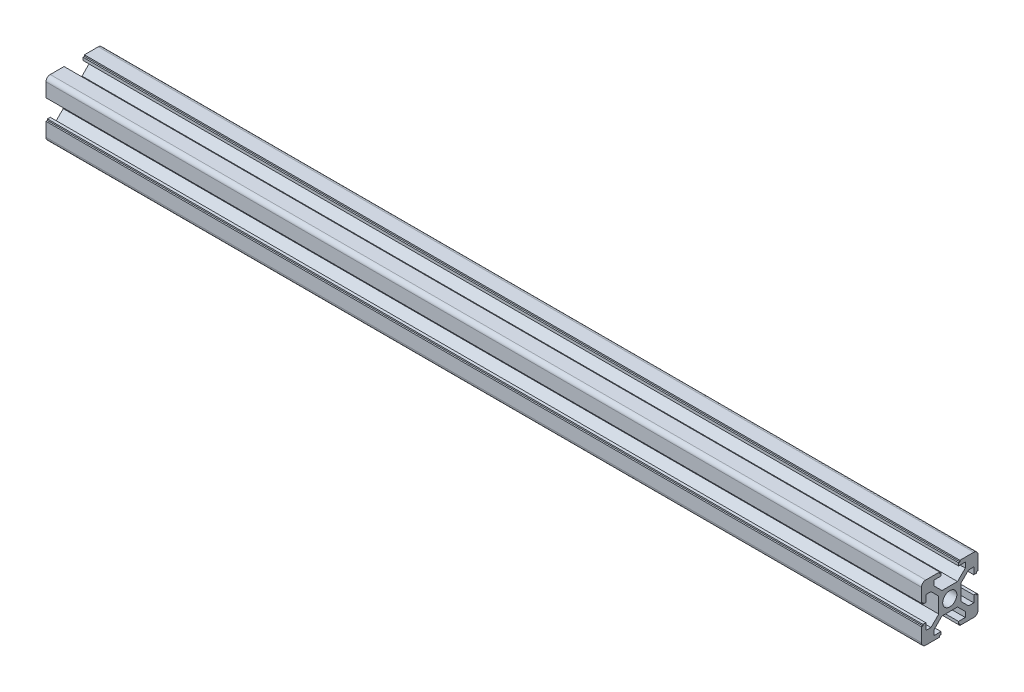
SolidWorks part; units mm, degrees
ref_plane "前视基准面" through (0, 0, 0) normal (0, 0, 1) x (1, 0, 0)
ref_plane "上视基准面" through (0, 0, 0) normal (0, 1, 0) x (1, 0, 0)
ref_plane "右视基准面" through (0, 0, 0) normal (1, 0, 0) x (0, 0, -1)
sketch "草图1" plane through (0, 0, 0) normal (0, 1, 0) x (1, 0, 0)
  line L0 (0, 0) -> (310, 0)
  dimension "D1" = 310
other "铝型材 20 X 20 X R1.5(1)"
ref_plane "基准面1" through (0, 0, 0) normal (1, 0, 0) x (0, 0, -1)
sketch "Sketch1" plane through (0, 0, 0) normal (1, 0, 0) x (0, 0, -1)
  line L0 (-3.6, 10) -> (-3.6, 9.5)
  line L1 (-3.6, 9.5) -> (-3.1, 9.5)
  line L2 (-3.1, 9.5) -> (-3.1, 8.5)
  line L3 (-3.1, 8.5) -> (-5.5, 8.5)
  line L4 (-8.5, -10) -> (-3.6, -10)
  line L5 (-10, -8.5) -> (-10, -3.6)
  line L6 (8.5, 10) -> (3.6, 10)
  line L7 (10, 8.5) -> (10, 3.6)
  line L8 (0, 14.8756) -> (0, 0) construction
  line L9 (0, 0) -> (14.1675, 0) construction
  line L10 (-5.5, 8.5) -> (-5.5, 6.65)
  line L11 (-5.5, 6.65) -> (-2.75, 3.9)
  line L12 (-2.75, 3.9) -> (2.75, 3.9)
  line L13 (5.5, 6.65) -> (2.75, 3.9)
  line L14 (5.5, 8.5) -> (5.5, 6.65)
  line L15 (3.1, 8.5) -> (5.5, 8.5)
  line L16 (3.1, 9.5) -> (3.1, 8.5)
  line L17 (3.6, 9.5) -> (3.1, 9.5)
  line L18 (3.6, 10) -> (3.6, 9.5)
  line L19 (-3.6, 10) -> (-8.5, 10)
  line L20 (10, 3.6) -> (9.5, 3.6)
  line L21 (9.5, 3.6) -> (9.5, 3.1)
  line L22 (9.5, 3.1) -> (8.5, 3.1)
  line L23 (8.5, 3.1) -> (8.5, 5.5)
  line L24 (8.5, 5.5) -> (6.65, 5.5)
  line L25 (6.65, 5.5) -> (3.9, 2.75)
  line L26 (3.9, 2.75) -> (3.9, -2.75)
  line L27 (6.65, -5.5) -> (3.9, -2.75)
  line L28 (8.5, -5.5) -> (6.65, -5.5)
  line L29 (8.5, -3.1) -> (8.5, -5.5)
  line L30 (9.5, -3.1) -> (8.5, -3.1)
  line L31 (9.5, -3.6) -> (9.5, -3.1)
  line L32 (10, -3.6) -> (9.5, -3.6)
  line L33 (3.6, -10) -> (3.6, -9.5)
  line L34 (3.6, -9.5) -> (3.1, -9.5)
  line L35 (3.1, -9.5) -> (3.1, -8.5)
  line L36 (3.1, -8.5) -> (5.5, -8.5)
  line L37 (5.5, -8.5) -> (5.5, -6.65)
  line L38 (5.5, -6.65) -> (2.75, -3.9)
  line L39 (2.75, -3.9) -> (-2.75, -3.9)
  line L40 (-5.5, -6.65) -> (-2.75, -3.9)
  line L41 (-5.5, -8.5) -> (-5.5, -6.65)
  line L42 (-3.1, -8.5) -> (-5.5, -8.5)
  line L43 (-3.1, -9.5) -> (-3.1, -8.5)
  line L44 (-3.6, -9.5) -> (-3.1, -9.5)
  line L45 (-3.6, -10) -> (-3.6, -9.5)
  line L46 (-10, -3.6) -> (-9.5, -3.6)
  line L47 (-9.5, -3.6) -> (-9.5, -3.1)
  line L48 (-9.5, -3.1) -> (-8.5, -3.1)
  line L49 (-8.5, -3.1) -> (-8.5, -5.5)
  line L50 (-8.5, -5.5) -> (-6.65, -5.5)
  line L51 (-6.65, -5.5) -> (-3.9, -2.75)
  line L52 (-3.9, -2.75) -> (-3.9, 2.75)
  line L53 (-6.65, 5.5) -> (-3.9, 2.75)
  line L54 (-8.5, 5.5) -> (-6.65, 5.5)
  line L55 (-8.5, 3.1) -> (-8.5, 5.5)
  line L56 (-9.5, 3.1) -> (-8.5, 3.1)
  line L57 (-9.5, 3.6) -> (-9.5, 3.1)
  line L58 (-10, 3.6) -> (-9.5, 3.6)
  line L59 (3.6, -10) -> (8.5, -10)
  line L60 (-10, 3.6) -> (-10, 8.5)
  line L61 (10, -3.6) -> (10, -8.5)
  circle A0 centre (0, 0) radius 2.5
  arc A1 (-10, 8.5) -> (-8.5, 10) centre (-8.5, 8.5) cw
  arc A2 (10, 8.5) -> (8.5, 10) centre (8.5, 8.5) ccw
  arc A3 (-8.5, -10) -> (-10, -8.5) centre (-8.5, -8.5) cw
  arc A4 (8.5, -10) -> (10, -8.5) centre (8.5, -8.5) ccw
  point P0 (-10, 0)
  point P1 (10, 0)
  point P2 (0, 10)
  point P3 (0, -10)
  point P4 (0, 0)
  point P5 (-10, -10)
  point P6 (10, -10)
  point P7 (10, 10)
  point P8 (-10, 10)
  point P13 (0, 0)
  point P36 (-10, 10)
  point P39 (10, 10)
  dimension "D1" = 11
  dimension "D2" = 20
  dimension "D3" = 6.2
  dimension "D4" = 7.2
  dimension "D5" = 6.1
  dimension "D6" = 5
  dimension "D7" = 1.5
  dimension "D8" = 45
  dimension "D9" = 0.5
  dimension "D10" = 1
  dimension "D11" = 5.5
